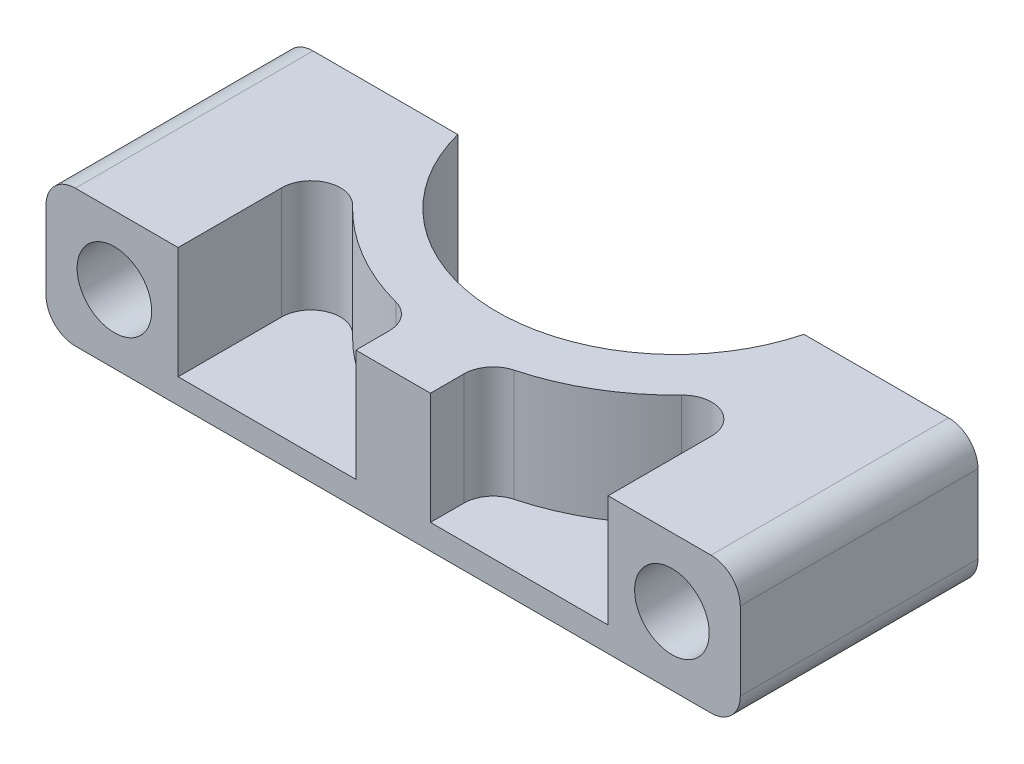
SolidWorks part; units mm, degrees
material "6061-T6 (SS)"
ref_plane "Front Plane" through (0, 0, 0) normal (0, 0, 1) x (1, 0, 0)
ref_plane "Top Plane" through (0, 0, 0) normal (0, 1, 0) x (1, 0, 0)
ref_plane "Right Plane" through (0, 0, 0) normal (1, 0, 0) x (0, 0, -1)
sketch "Sketch1" plane through (0, 0, 0) normal (0, 1, 0) x (1, 0, 0)
  line L0 (-27.9162, -22.7194) -> (27.9162, -22.7194)
  line L2 (-27.9162, -22.7194) -> (-27.9162, -3.6027)
  line L3 (-27.9162, -3.6027) -> (-13.9162, -3.6027)
  line L4 (27.9162, -22.7194) -> (27.9162, -3.6027)
  line L5 (-21.6243, -22.7194) -> (27.9162, -3.6027) construction
  line L6 (-27.9162, -3.6027) -> (21.6243, -22.7194) construction
  line L7 (13.9162, -3.6027) -> (27.9162, -3.6027)
  arc A0 (-13.9162, -3.6027) -> (13.9162, -3.6027) centre (0, 0) ccw
  point P3 (0, -14.375)
  dimension "D1" = 28.75
  dimension "D2" = 14
  dimension "D3" = 14
extrude "Boss-Extrude1" add sketch "Sketch1" along normal blind 11
sketch "Sketch2" plane through (0, 0, 3.6027) normal (0, 0, -1) x (-1, 0, 0)
  line L0 (22.4162, 5.5) -> (27.9162, 5.5) construction
  line L2 (27.9162, 11) -> (27.9162, 0) construction
  line L4 (-22.4162, 5.5) -> (-27.9162, 5.5) construction
  line L8 (-27.9162, 11) -> (-27.9162, 0) construction
  line L9 (-27.9162, 5.5) -> (-27.9162, 0) construction
  circle A0 centre (22.4162, 5.5) radius 3
  circle A1 centre (-22.4162, 5.5) radius 3
extrude "Cut-Extrude1" cut sketch "Sketch2" against normal blind 30
sketch "Sketch3" plane through (0, 11, 0) normal (0, 1, 0) x (1, 0, 0)
  line L0 (0, -22.7194) -> (0, -16.3694) construction
  line L1 (-27.9162, -22.7194) -> (27.9162, -22.7194) construction
  line L3 (-17.2886, -22.7194) -> (17.2886, -22.7194)
  line L7 (-17.2886, -22.5163) -> (0, -19.5444) construction
  line L8 (0, -19.5444) -> (17.7886, -22.6022) construction
  line L14 (3, -22.7194) -> (3, -18.1284)
  line L15 (-3, -22.7194) -> (-3, -18.1284)
  line L16 (3, -22.7194) -> (3, -16.3694) construction
  line L17 (-3, -22.7194) -> (-3, -16.3694) construction
  line L18 (17.2886, -6.2246) -> (17.2886, -22.7194)
  line L19 (-17.2886, -6.2246) -> (-17.2886, -22.7194)
  arc A2 (-17.7886, -4.6051) -> (17.7886, -4.6051) centre (0, 0) ccw
  arc A3 (-17.2886, -6.2246) -> (17.2886, -6.2246) centre (0, 0) ccw
  point P5 (0, -19.5444)
  point P26 (0, 0)
  point P27 (0, 0)
  dimension "D1" = 4
  dimension "D2" = 3
  dimension "D3" = 3
extrude "Cut-Extrude3" cut sketch "Sketch3" against normal blind 9
fillet "Fillet2" radius 2.36 4 edges at (-3, 6.5, 18.1284) (3, 6.5, 18.1284) (-17.2886, 6.5, 6.2246) (17.2886, 6.5, 6.2246)
fillet "Fillet3" radius 2.36 4 edges at (-27.9162, 11, 13.161) (-27.9162, 0, 13.161) (27.9162, 11, 13.161) (27.9162, 0, 13.161)
